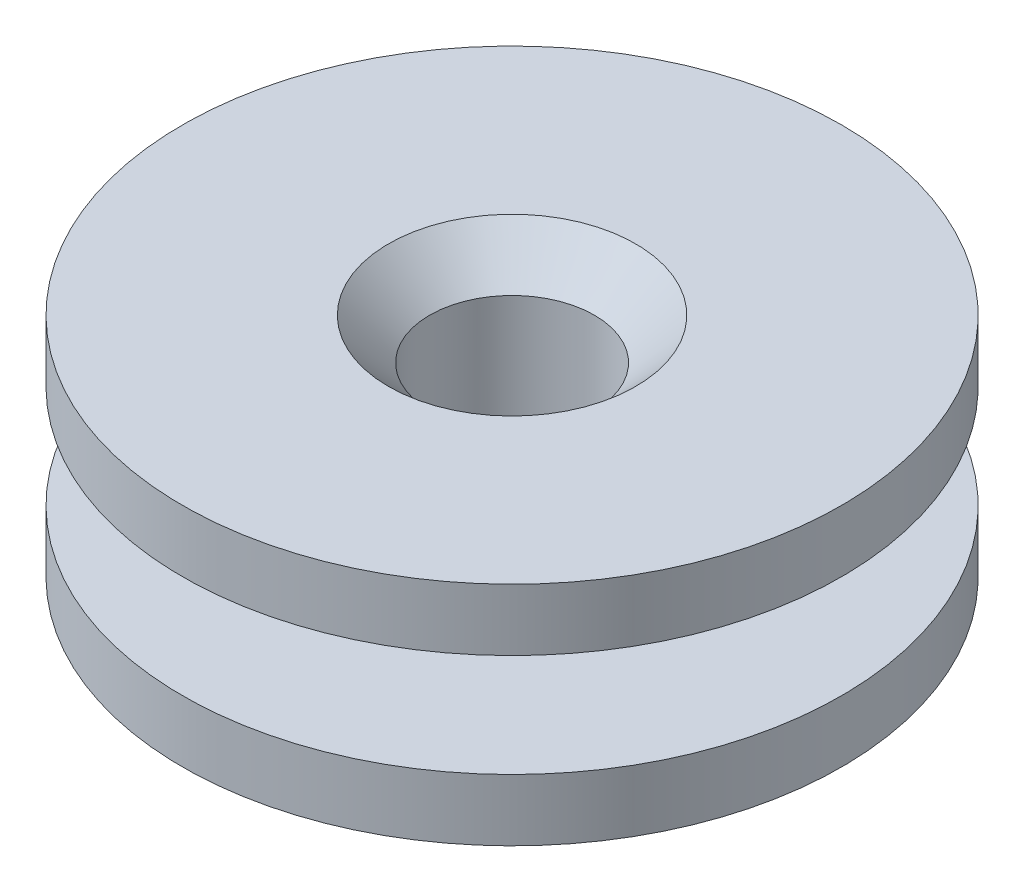
SolidWorks part; units mm, degrees
ref_plane "Front Plane" through (0, 0, 0) normal (0, 0, 1) x (1, 0, 0)
ref_plane "Top Plane" through (0, 0, 0) normal (0, 1, 0) x (1, 0, 0)
ref_plane "Right Plane" through (0, 0, 0) normal (1, 0, 0) x (0, 0, -1)
sketch "Sketch1" plane through (0, 0, 0) normal (0, 0, 1) x (1, 0, 0)
  line L0 (4, 0) -> (4, 11)
  line L1 (4, 11) -> (16, 11)
  line L2 (16, 11) -> (16, 8)
  line L3 (16, 8) -> (8, 8)
  line L4 (8, 8) -> (8, 3)
  line L5 (8, 3) -> (16, 3)
  line L6 (16, 3) -> (16, 0)
  line L7 (16, 0) -> (4, 0)
  line L8 (0, 0) -> (0, 17.7633) construction
  line L9 (0, 0) -> (-2.3464, 0) construction
  dimension "D1" = 8
  dimension "D2" = 16
  dimension "D3" = 11
  dimension "D4" = 3
  dimension "D5" = 3
  dimension "D6" = 4
revolve "Revolve1" add sketch "Sketch1" angle 360 about L8
chamfer "Chamfer1" distance 2 angle 45 2 edges at (0, 0, -4) (0, 11, -4)
